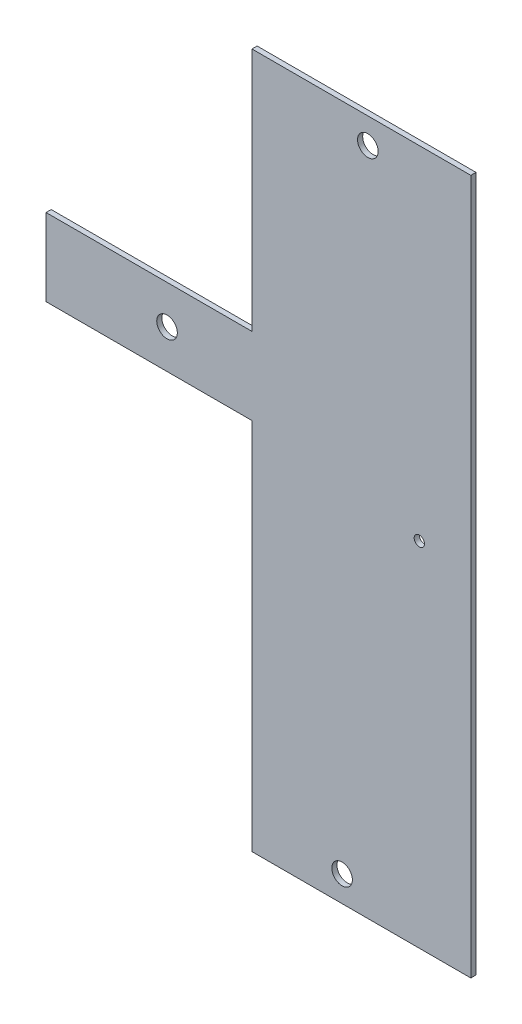
SolidWorks part; units mm, degrees
ref_plane "Front Plane" through (0, 0, 0) normal (0, 0, 1) x (1, 0, 0)
ref_plane "Top Plane" through (0, 0, 0) normal (0, 1, 0) x (1, 0, 0)
ref_plane "Right Plane" through (0, 0, 0) normal (1, 0, 0) x (0, 0, -1)
sketch "Sketch2" plane through (0, 0, 0) normal (0, 0, 1) x (1, 0, 0)
  line L0 (-71.5961, 14.6032) -> (8.4039, 14.6032)
  line L1 (8.4039, 14.6032) -> (8.4039, 109.6032)
  line L2 (8.4039, 109.6032) -> (93.4039, 109.6032)
  line L3 (93.4039, 109.6032) -> (93.4039, -160.3968)
  line L4 (93.4039, -160.3968) -> (8.4039, -160.3968)
  line L5 (8.4039, -160.3968) -> (8.4039, -15.3968)
  line L6 (8.4039, -15.3968) -> (-71.5961, -15.3968)
  line L7 (-71.5961, -15.3968) -> (-71.5961, 14.6032)
  dimension "D1" = 10
  dimension "D2" = 40
  dimension "D3" = 10
  dimension "D4" = 45
  dimension "D5" = 95
  dimension "D6" = 30
  dimension "D7" = 80
extrude "Extrude2" add sketch "Sketch2" along normal blind 2
sketch "Sketch3" plane through (0, 0, 0) normal (0, 0, -1) x (-1, 0, 0)
  circle A0 centre (-53.4039, 99.6032) radius 4
  circle A1 centre (24.5961, -0.3968) radius 4
  circle A2 centre (-73.404, -23.3968) radius 2
  circle A3 centre (-43.4039, -150.3968) radius 4
extrude "Cut-Extrude1" cut sketch "Sketch3" against normal blind 2
